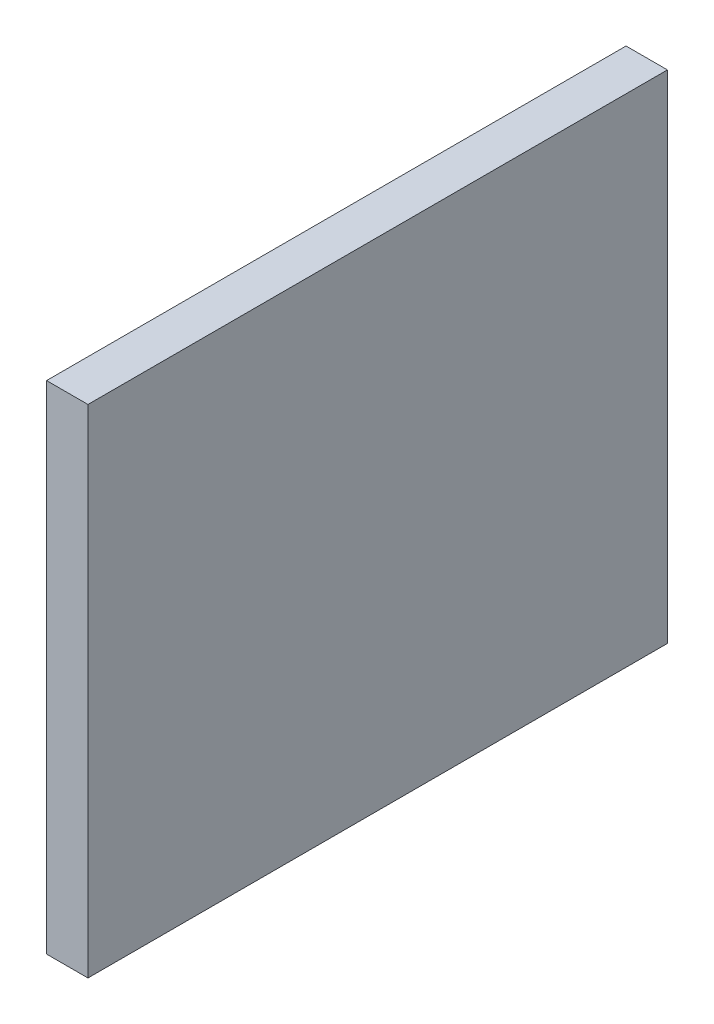
SolidWorks part; units mm, degrees
ref_plane "Front Plane" through (0, 0, 0) normal (0, 0, 1) x (1, 0, 0)
ref_plane "Top Plane" through (0, 0, 0) normal (0, 1, 0) x (1, 0, 0)
ref_plane "Right Plane" through (0, 0, 0) normal (1, 0, 0) x (0, 0, -1)
sketch "Sketch1" plane through (0, 0, 0) normal (1, 0, 0) x (0, 0, -1)
  line L1 (0, 0) -> (70, 0)
  line L2 (0, 0) -> (0, -60)
  line L3 (0, -60) -> (70, -60)
  line L4 (70, 0) -> (70, -60)
  dimension "D1" = 60
  dimension "D2" = 70
extrude "Boss-Extrude1" add sketch "Sketch1" along normal blind 5
